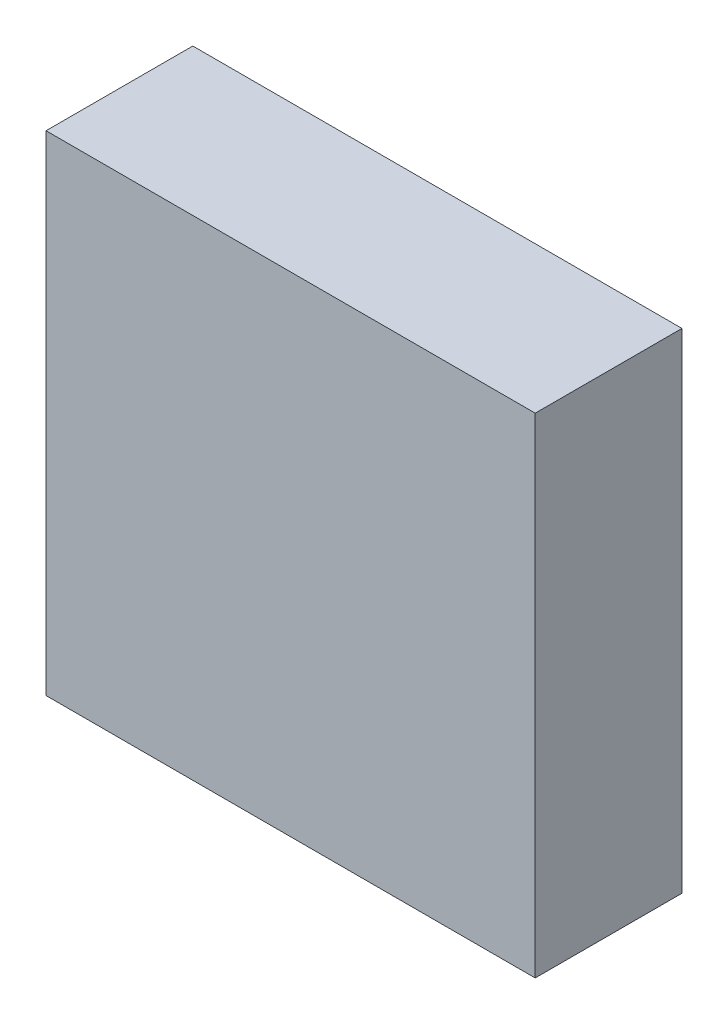
SolidWorks part; units mm, degrees
material "Acrylic (Medium-high impact)"
ref_plane "Front Plane" through (0, 0, 0) normal (0, 0, 1) x (1, 0, 0)
ref_plane "Top Plane" through (0, 0, 0) normal (0, 1, 0) x (1, 0, 0)
ref_plane "Right Plane" through (0, 0, 0) normal (1, 0, 0) x (0, 0, -1)
sketch "Sketch1" plane through (0, 0, 0) normal (0, 0, 1) x (1, 0, 0)
  line L1 (0, 0) -> (10, 0)
  line L2 (0, 0) -> (0, 10)
  line L3 (0, 10) -> (10, 10)
  line L4 (10, 0) -> (10, 10)
  dimension "D1" = 10
extrude "Boss-Extrude1" add sketch "Sketch1" along normal blind 3
